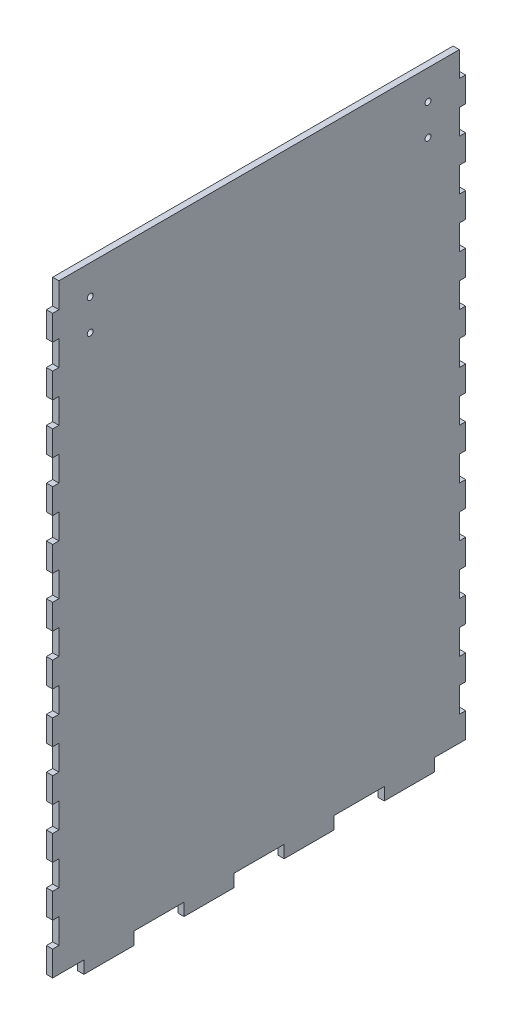
SolidWorks part; units mm, degrees
ref_plane "Front Plane" through (0, 0, 0) normal (0, 0, 1) x (1, 0, 0)
ref_plane "Top Plane" through (0, 0, 0) normal (0, 1, 0) x (1, 0, 0)
ref_plane "Right Plane" through (0, 0, 0) normal (1, 0, 0) x (0, 0, -1)
sketch "Sketch1" plane through (0, 0, 0) normal (1, 0, 0) x (0, 0, -1)
  line L0 (0, 0) -> (203.2, 0)
  line L1 (203.2, 0) -> (203.2, 304.8)
  line L2 (203.2, 304.8) -> (0, 304.8)
  line L3 (0, 304.8) -> (0, 0)
  line L4 (101.6, 304.8) -> (101.6, 0) construction
  line L5 (0, 0) -> (-3.175, 0)
  line L6 (-3.175, 0) -> (-3.175, 12.7)
  line L7 (-3.175, 12.7) -> (0, 12.7)
  line L8 (0, 12.7) -> (0, 0)
  line L9 (0, 25.4) -> (-3.175, 25.4)
  line L10 (-3.175, 25.4) -> (-3.175, 38.1)
  line L11 (-3.175, 38.1) -> (0, 38.1)
  line L12 (0, 38.1) -> (0, 25.4)
  line L13 (0, 50.8) -> (-3.175, 50.8)
  line L14 (-3.175, 50.8) -> (-3.175, 63.5)
  line L15 (-3.175, 63.5) -> (0, 63.5)
  line L16 (0, 63.5) -> (0, 50.8)
  line L17 (0, 76.2) -> (-3.175, 76.2)
  line L18 (-3.175, 76.2) -> (-3.175, 88.9)
  line L19 (-3.175, 88.9) -> (0, 88.9)
  line L20 (0, 88.9) -> (0, 76.2)
  line L21 (0, 101.6) -> (-3.175, 101.6)
  line L22 (-3.175, 101.6) -> (-3.175, 114.3)
  line L23 (-3.175, 114.3) -> (0, 114.3)
  line L24 (0, 114.3) -> (0, 101.6)
  line L25 (0, 127) -> (-3.175, 127)
  line L26 (-3.175, 127) -> (-3.175, 139.7)
  line L27 (-3.175, 139.7) -> (0, 139.7)
  line L28 (0, 139.7) -> (0, 127)
  line L29 (0, 152.4) -> (-3.175, 152.4)
  line L30 (-3.175, 152.4) -> (-3.175, 165.1)
  line L31 (-3.175, 165.1) -> (0, 165.1)
  line L32 (0, 165.1) -> (0, 152.4)
  line L33 (0, 177.8) -> (-3.175, 177.8)
  line L34 (-3.175, 177.8) -> (-3.175, 190.5)
  line L35 (-3.175, 190.5) -> (0, 190.5)
  line L36 (0, 190.5) -> (0, 177.8)
  line L37 (0, 203.2) -> (-3.175, 203.2)
  line L38 (-3.175, 203.2) -> (-3.175, 215.9)
  line L39 (-3.175, 215.9) -> (0, 215.9)
  line L40 (0, 215.9) -> (0, 203.2)
  line L41 (0, 228.6) -> (-3.175, 228.6)
  line L42 (-3.175, 228.6) -> (-3.175, 241.3)
  line L43 (-3.175, 241.3) -> (0, 241.3)
  line L44 (0, 241.3) -> (0, 228.6)
  line L45 (0, 254) -> (-3.175, 254)
  line L46 (-3.175, 254) -> (-3.175, 266.7)
  line L47 (-3.175, 266.7) -> (0, 266.7)
  line L48 (0, 266.7) -> (0, 254)
  line L49 (0, 279.4) -> (-3.175, 279.4)
  line L50 (-3.175, 279.4) -> (-3.175, 292.1)
  line L51 (-3.175, 292.1) -> (0, 292.1)
  line L52 (0, 292.1) -> (0, 279.4)
  line L53 (0, 0) -> (0, 25.4) construction
  line L54 (12.7, 0) -> (12.7, -6.35)
  line L55 (12.7, -6.35) -> (38.1, -6.35)
  line L56 (38.1, -6.35) -> (38.1, 0)
  line L57 (38.1, 0) -> (12.7, 0)
  line L58 (88.9, 0) -> (63.5, 0)
  line L59 (63.5, 0) -> (63.5, -6.35)
  line L60 (63.5, -6.35) -> (88.9, -6.35)
  line L61 (88.9, -6.35) -> (88.9, 0)
  line L62 (139.7, 0) -> (114.3, 0)
  line L63 (114.3, 0) -> (114.3, -6.35)
  line L64 (114.3, -6.35) -> (139.7, -6.35)
  line L65 (139.7, -6.35) -> (139.7, 0)
  line L66 (190.5, 0) -> (165.1, 0)
  line L67 (165.1, 0) -> (165.1, -6.35)
  line L68 (165.1, -6.35) -> (190.5, -6.35)
  line L69 (190.5, -6.35) -> (190.5, 0)
  line L70 (38.1, 0) -> (88.9, 0) construction
  line L71 (203.2, 12.7) -> (203.2, 0)
  line L72 (206.375, 12.7) -> (203.2, 12.7)
  line L73 (206.375, 0) -> (206.375, 12.7)
  line L74 (203.2, 0) -> (206.375, 0)
  line L75 (203.2, 38.1) -> (203.2, 25.4)
  line L76 (206.375, 38.1) -> (203.2, 38.1)
  line L77 (206.375, 25.4) -> (206.375, 38.1)
  line L78 (203.2, 25.4) -> (206.375, 25.4)
  line L79 (203.2, 63.5) -> (203.2, 50.8)
  line L80 (206.375, 63.5) -> (203.2, 63.5)
  line L81 (206.375, 50.8) -> (206.375, 63.5)
  line L82 (203.2, 50.8) -> (206.375, 50.8)
  line L83 (203.2, 88.9) -> (203.2, 76.2)
  line L84 (206.375, 88.9) -> (203.2, 88.9)
  line L85 (206.375, 76.2) -> (206.375, 88.9)
  line L86 (203.2, 76.2) -> (206.375, 76.2)
  line L87 (203.2, 114.3) -> (203.2, 101.6)
  line L88 (206.375, 114.3) -> (203.2, 114.3)
  line L89 (206.375, 101.6) -> (206.375, 114.3)
  line L90 (203.2, 101.6) -> (206.375, 101.6)
  line L91 (203.2, 139.7) -> (203.2, 127)
  line L92 (206.375, 139.7) -> (203.2, 139.7)
  line L93 (206.375, 127) -> (206.375, 139.7)
  line L94 (203.2, 127) -> (206.375, 127)
  line L95 (203.2, 165.1) -> (203.2, 152.4)
  line L96 (206.375, 165.1) -> (203.2, 165.1)
  line L97 (206.375, 152.4) -> (206.375, 165.1)
  line L98 (203.2, 152.4) -> (206.375, 152.4)
  line L99 (203.2, 190.5) -> (203.2, 177.8)
  line L100 (206.375, 190.5) -> (203.2, 190.5)
  line L101 (206.375, 177.8) -> (206.375, 190.5)
  line L102 (203.2, 177.8) -> (206.375, 177.8)
  line L103 (203.2, 215.9) -> (203.2, 203.2)
  line L104 (206.375, 215.9) -> (203.2, 215.9)
  line L105 (206.375, 203.2) -> (206.375, 215.9)
  line L106 (203.2, 203.2) -> (206.375, 203.2)
  line L107 (203.2, 241.3) -> (203.2, 228.6)
  line L108 (206.375, 241.3) -> (203.2, 241.3)
  line L109 (206.375, 228.6) -> (206.375, 241.3)
  line L110 (203.2, 228.6) -> (206.375, 228.6)
  line L111 (203.2, 266.7) -> (203.2, 254)
  line L112 (206.375, 266.7) -> (203.2, 266.7)
  line L113 (206.375, 254) -> (206.375, 266.7)
  line L114 (203.2, 254) -> (206.375, 254)
  line L115 (203.2, 292.1) -> (203.2, 279.4)
  line L116 (206.375, 292.1) -> (203.2, 292.1)
  line L117 (206.375, 279.4) -> (206.375, 292.1)
  line L118 (203.2, 279.4) -> (206.375, 279.4)
  dimension "D1" = 203.2
  dimension "D2" = 304.8
  dimension "D3" = 3.175
  dimension "D4" = 12.7
  dimension "D6" = 25.4
  dimension "D7" = 6.35
  dimension "D8" = 25.4
  dimension "D9" = 12.7
  dimension "D11" = 50.8
  dimension "D5" = 12
  dimension "D10" = 4
extrude "Boss-Extrude1" add sketch "Sketch1" along normal blind 3.175 contours L51 L50 L49 L3 | L47 L46 L45 L3 | L43 L42 L41 L3 | L39 L38 L37 L3 | L35 L34 L33 L3 | L31 L30 L29 L3 | L27 L26 L25 L3 | L23 L22 L21 L3 | L19 L18 L17 L3 | L15 L14 L13 L3 | L11 L10 L9 L3 | L2 L3 L0 L1 | L7 L6 L5 L3 | L55 L56 L0 L54 | L60 L61 L0 L59 | L64 L65 L0 L63 | L68 L69 L0 L67 | L1 L74 L73 L72 | L1 L78 L77 L76 | L1 L82 L81 L80 | L1 L86 L85 L84 | L1 L90 L89 L88 | L1 L94 L93 L92 | L1 L98 L97 L96 | L1 L102 L101 L100 | L1 L106 L105 L104 | L1 L110 L109 L108 | L1 L114 L113 L112 | L1 L118 L117 L116
sketch "Sketch2" plane through (3.175, 0, 0) normal (1, 0, 0) x (0, 0, -1)
  line L1 (203.2, 304.8) -> (0, 304.8) construction
  line L2 (101.6, 304.8) -> (101.6, 0) construction
  line L3 (88.9, 0) -> (114.3, 0) construction
  line L4 (-3.175, 279.4) -> (-3.175, 292.1) construction
  circle A0 centre (15.875, 289.8) radius 1.5
  circle A1 centre (15.875, 274.05) radius 1.5
  circle A2 centre (187.325, 274.05) radius 1.5
  circle A3 centre (187.325, 289.8) radius 1.5
  dimension "D1" = 3
  dimension "D2" = 3
  dimension "D3" = 19.05
  dimension "D4" = 15.75
  dimension "D5" = 15
extrude "Cut-Extrude1" cut sketch "Sketch2" against normal up to surface (3.175 mm away) up to face at (0, 130.175, -101.6)
equation "\"wall_thickness\"= 0.125in"
equation "\"base_thickness\"= 0.25in"
equation "\"D3@Sketch1\"=\"wall_thickness\""
equation "\"D7@Sketch1\"=\"base_thickness\""
equation "\"D1@Boss-Extrude1\"=\"wall_thickness\""
